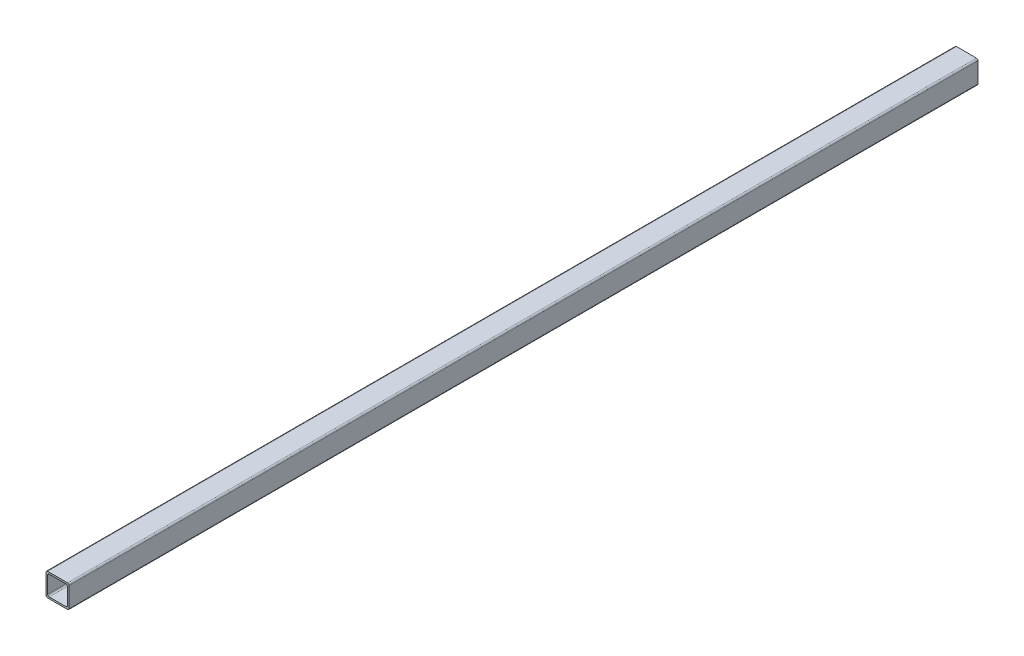
SolidWorks part; units mm, degrees
material "ASTM A500 Grade B Steel"
ref_plane "Front Plane" through (0, 0, 0) normal (0, 0, 1) x (1, 0, 0)
ref_plane "Top Plane" through (0, 0, 0) normal (0, 1, 0) x (1, 0, 0)
ref_plane "Right Plane" through (0, 0, 0) normal (1, 0, 0) x (0, 0, -1)
sketch "Sketch1" plane through (0, 0, 0) normal (0, 0, 1) x (1, 0, 0)
  line L0 (5.3086, -2.7686) -> (32.7914, -2.7686)
  line L1 (2.54, 0) -> (35.56, 0)
  line L2 (0, -2.54) -> (0, -35.56)
  line L3 (2.54, -38.1) -> (35.56, -38.1)
  line L4 (38.1, -2.54) -> (38.1, -35.56)
  line L5 (35.3314, -5.3086) -> (35.3314, -32.7914)
  line L6 (5.3086, -35.3314) -> (32.7914, -35.3314)
  line L7 (2.7686, -5.3086) -> (2.7686, -32.7914)
  line L8 (0, 0) -> (0, -38.1) construction
  line L9 (0, -38.1) -> (38.1, -38.1) construction
  line L10 (38.1, 0) -> (38.1, -38.1) construction
  line L11 (2.7686, -2.7686) -> (2.7686, -35.3314) construction
  line L12 (2.7686, -35.3314) -> (35.3314, -35.3314) construction
  line L13 (35.3314, -2.7686) -> (35.3314, -35.3314) construction
  line L14 (2.7686, -2.7686) -> (35.3314, -2.7686) construction
  line L15 (0, 0) -> (38.1, 0) construction
  arc A0 (0, -35.56) -> (2.54, -38.1) centre (2.54, -35.56) ccw
  arc A1 (38.1, -35.56) -> (35.56, -38.1) centre (35.56, -35.56) cw
  arc A2 (2.7686, -32.7914) -> (5.3086, -35.3314) centre (5.3086, -32.7914) ccw
  arc A3 (32.7914, -35.3314) -> (35.3314, -32.7914) centre (32.7914, -32.7914) ccw
  arc A4 (35.3314, -5.3086) -> (32.7914, -2.7686) centre (32.7914, -5.3086) ccw
  arc A5 (38.1, -2.54) -> (35.56, 0) centre (35.56, -2.54) ccw
  arc A6 (0, -2.54) -> (2.54, 0) centre (2.54, -2.54) cw
  arc A7 (5.3086, -2.7686) -> (2.7686, -5.3086) centre (5.3086, -5.3086) ccw
  point P12 (0, -38.1)
  dimension "D4" = 2.54
  dimension "D3" = 2.7686
extrude "Boss-Extrude1" add sketch "Sketch1" along normal blind 1500
